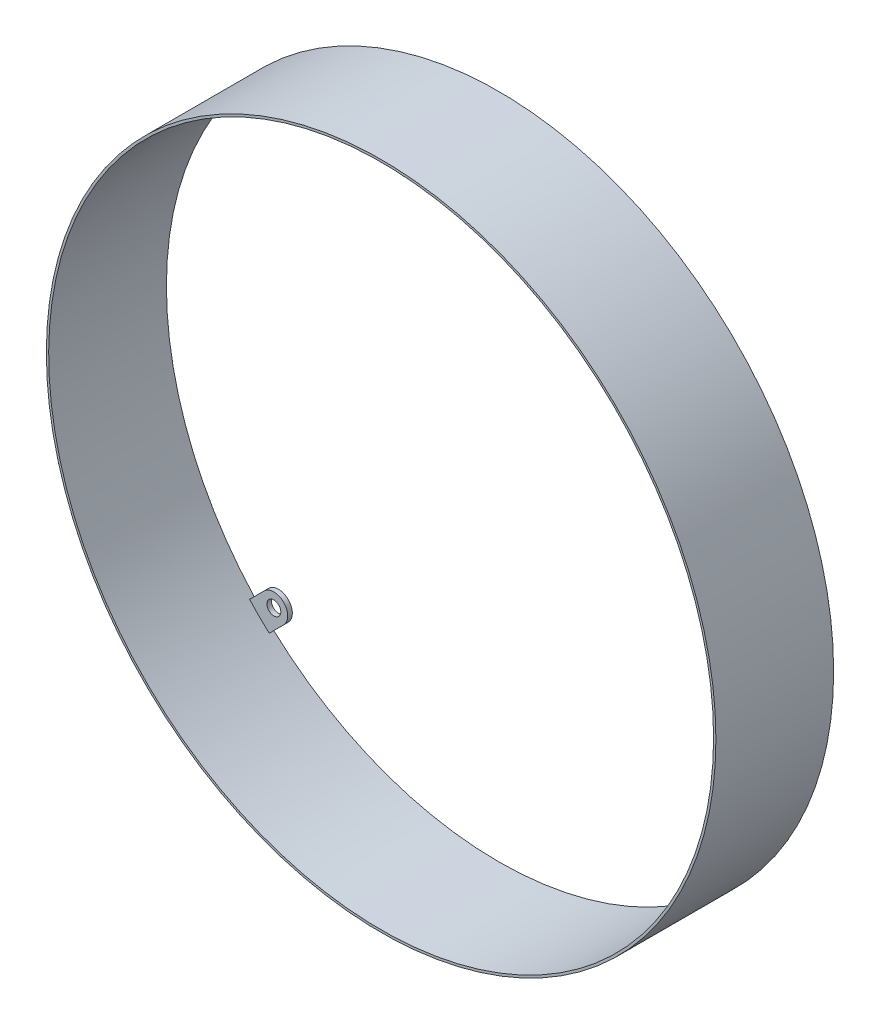
SolidWorks part; units mm, degrees
material "ABS"
ref_plane "Ebene vorne" through (0, 0, 0) normal (0, 0, 1) x (1, 0, 0)
ref_plane "Ebene oben" through (0, 0, 0) normal (0, 1, 0) x (1, 0, 0)
ref_plane "Ebene rechts" through (0, 0, 0) normal (1, 0, 0) x (0, 0, -1)
sketch "Skizze1" plane through (0, 0, 0) normal (0, 0, 1) x (1, 0, 0)
  circle A0 centre (0, 0) radius 72.5
  circle A1 centre (0, 0) radius 72
  dimension "D1" = 145
  dimension "D2" = 0.5
extrude "Cover Ring" add sketch "Skizze1" along normal blind 25.5
sketch "Skizze2" plane through (0, 0, 0) normal (0, 0, 1) x (1, 0, 0)
  line L0 (0, 0) -> (51.2652, 51.2652) construction
  line L1 (0, 0) -> (72.5, 0) construction
  line L2 (45.6084, 49.851) -> (48.7904, 53.033)
  line L3 (45.6084, 49.851) -> (49.851, 45.6084)
  line L4 (48.7904, 53.033) -> (53.033, 48.7904)
  line L5 (49.851, 45.6084) -> (53.033, 48.7904)
  line L6 (45.6084, 49.851) -> (53.033, 48.7904) construction
  line L7 (48.7904, 53.033) -> (49.851, 45.6084) construction
  circle A0 centre (0, 0) radius 67.5 construction
  circle A1 centre (0, 0) radius 72.5 construction
  circle A2 centre (0, 0) radius 72 construction
  arc A3 (45.6084, 49.851) -> (49.851, 45.6084) centre (47.7297, 47.7297) ccw
  circle A4 centre (47.7297, 47.7297) radius 1.5
  point P9 (49.3207, 49.3207)
  dimension "D1" = 45
  dimension "D2" = 135
  dimension "D3" = 6
  dimension "D4" = 3
extrude "Spacer Screw" add sketch "Skizze2" along normal blind 1 contours A4 L3 L5 L4 L2 | A4 L3 A3
pattern_circular "Kreismuster1" count 4 over 360 about axis through (0, 0, 0) along (0, 0, 1) of "Spacer Screw"
